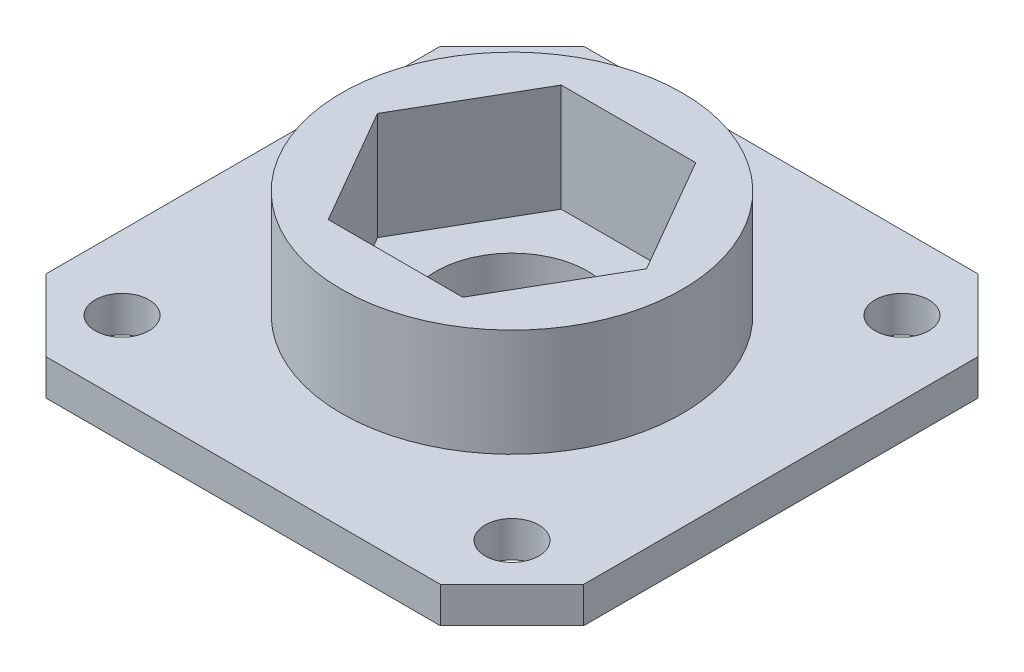
SolidWorks part; units mm, degrees
ref_plane "Front Plane" through (0, 0, 0) normal (0, 0, 1) x (1, 0, 0)
ref_plane "Top Plane" through (0, 0, 0) normal (0, 1, 0) x (1, 0, 0)
ref_plane "Right Plane" through (0, 0, 0) normal (1, 0, 0) x (0, 0, -1)
sketch "Sketch1" plane through (0, 0, 0) normal (0, 1, 0) x (1, 0, 0)
  line L0 (-15, 11) -> (-11, 15)
  line L1 (-11, -15) -> (11, -15)
  line L2 (-15, -11) -> (-15, 11)
  line L3 (-11, 15) -> (11, 15)
  line L4 (15, -11) -> (15, 11)
  line L5 (-15, -15) -> (15, 15) construction
  line L6 (-15, 15) -> (15, -15) construction
  line L7 (11, 15) -> (15, 11)
  line L8 (11, -15) -> (15, -11)
  line L9 (-15, -11) -> (-11, -15)
  circle A0 centre (0, 0) radius 4.25
  circle A1 centre (-10.8787, -10.8787) radius 1.5
  circle A2 centre (-10.8787, 10.8787) radius 1.5
  circle A3 centre (10.8787, 10.8787) radius 1.5
  circle A4 centre (10.8787, -10.8787) radius 1.5
  point P0 (0, 0)
  dimension "D7" = 8.5
  dimension "D8" = 3
  dimension "D1" = 30
  dimension "D2" = 30
  dimension "D9" = 3
extrude "Boss-Extrude1" add sketch "Sketch1" along normal blind 2
sketch "Sketch2" plane through (0, 2, 0) normal (0, 1, 0) x (1, 0, 0)
  line L1 (7.5056, 0) -> (3.7528, 6.5)
  line L2 (3.7528, 6.5) -> (-3.7528, 6.5)
  line L3 (-3.7528, 6.5) -> (-7.5056, 0)
  line L4 (-7.5056, 0) -> (-3.7528, -6.5)
  line L5 (-3.7528, -6.5) -> (3.7528, -6.5)
  line L6 (3.7528, -6.5) -> (7.5056, 0)
  circle A0 centre (0, 0) radius 9.5
  circle A1 centre (0, 0) radius 6.5 construction
  dimension "D1" = 13
  dimension "D2" = 3
extrude "Boss-Extrude2" add sketch "Sketch2" along normal blind 6
